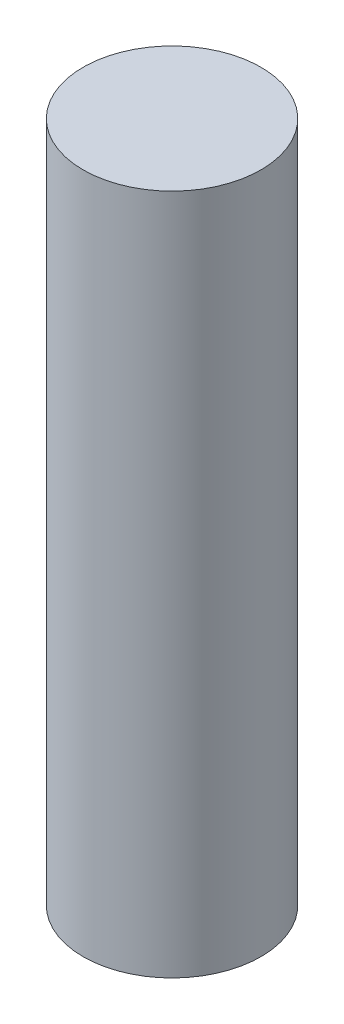
SolidWorks part; units mm, degrees
ref_plane "Front Plane" through (0, 0, 0) normal (0, 0, 1) x (1, 0, 0)
ref_plane "Top Plane" through (0, 0, 0) normal (0, 1, 0) x (1, 0, 0)
ref_plane "Right Plane" through (0, 0, 0) normal (1, 0, 0) x (0, 0, -1)
sketch "Sketch1" plane through (0, 0, 0) normal (0, 1, 0) x (1, 0, 0)
  line L0 (0, 0) -> (-109.2351, -37.0849) construction
  circle A0 centre (0, 45.445) radius 1.925
extrude "Boss-Extrude1" add sketch "Sketch1" along normal blind 14.75
